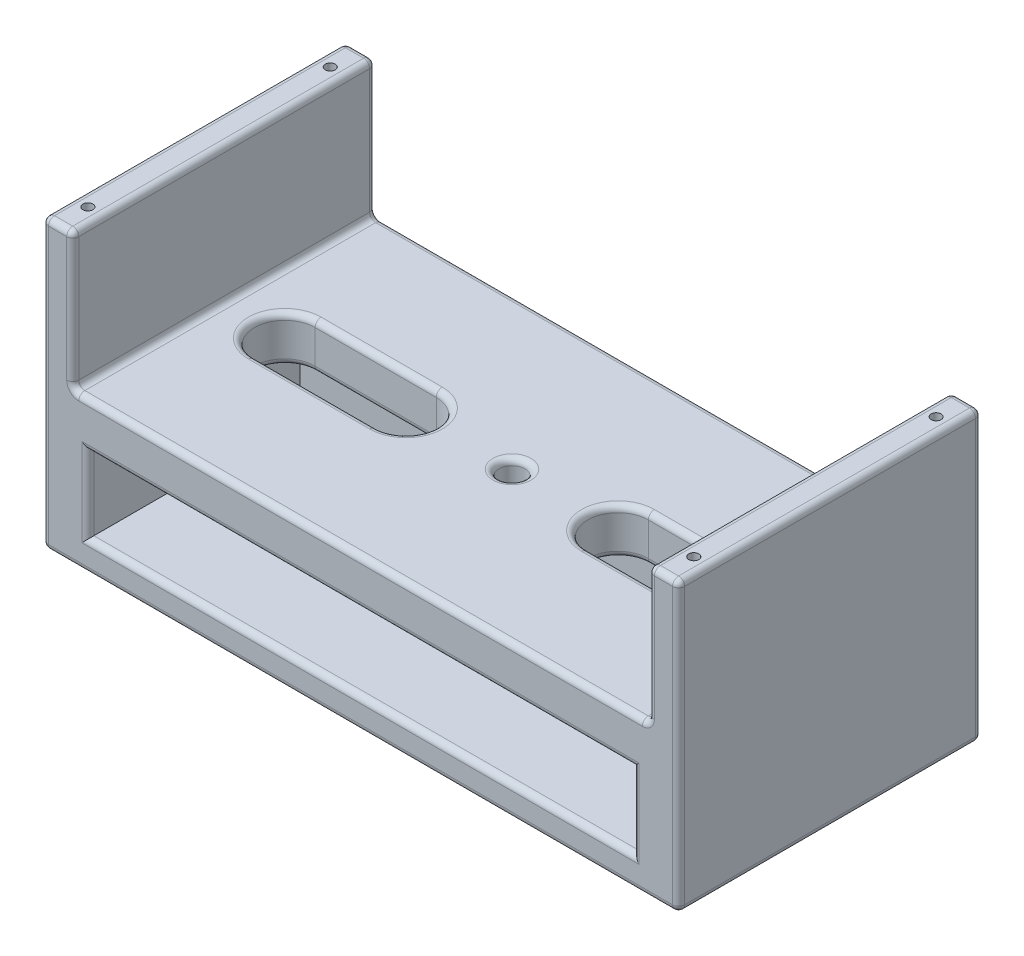
SolidWorks part; units mm, degrees
ref_plane "前视基准面" through (0, 0, 0) normal (0, 0, 1) x (1, 0, 0)
ref_plane "上视基准面" through (0, 0, 0) normal (0, 1, 0) x (1, 0, 0)
ref_plane "右视基准面" through (0, 0, 0) normal (1, 0, 0) x (0, 0, -1)
other "Configuration Table"
sketch "草图1" plane through (0, 0, 0) normal (0, 1, 0) x (1, 0, 0)
  line L1 (0, 0) -> (210, 0)
  line L2 (0, 0) -> (0, -100)
  line L3 (0, -100) -> (210, -100)
  line L4 (210, 0) -> (210, -100)
  dimension "D1" = 210
  dimension "D2" = 100
extrude "凸台-拉伸1" add sketch "草图1" along normal blind 50
sketch "草图2" plane through (0, 50, 0) normal (0, 1, 0) x (1, 0, 0)
  line L0 (0, -50) -> (210, -50) construction
  line L1 (0, 0) -> (0, -100) construction
  line L2 (210, -100) -> (210, 0) construction
  line L3 (105, 0) -> (105, -100) construction
  line L4 (210, 0) -> (0, 0) construction
  line L5 (0, -100) -> (210, -100) construction
  line L6 (30, -50) -> (70, -50) construction
  line L7 (30, -40) -> (70, -40)
  line L8 (30, -60) -> (70, -60)
  line L9 (140, -50) -> (180, -50) construction
  line L10 (140, -40) -> (180, -40)
  line L11 (140, -60) -> (180, -60)
  arc A0 (30, -40) -> (30, -60) centre (30, -50) ccw
  arc A1 (70, -60) -> (70, -40) centre (70, -50) ccw
  arc A2 (140, -40) -> (140, -60) centre (140, -50) ccw
  arc A3 (180, -60) -> (180, -40) centre (180, -50) ccw
  point P12 (105, -50)
  point P15 (50, -50)
  point P20 (160, -50)
  dimension "D3" = 10
  dimension "D1" = 35
  dimension "D2" = 40
  dimension "D4" = 35
extrude "切除-拉伸1" cut sketch "草图2" against normal blind 40
sketch "草图3" plane through (0, 0, 100) normal (0, 0, 1) x (1, 0, 0)
  line L0 (210, 50) -> (210, 0) construction
  line L1 (15, 10) -> (195, 10)
  line L2 (15, 10) -> (15, 35)
  line L3 (15, 35) -> (195, 35)
  line L4 (195, 10) -> (195, 35)
  line L5 (0, 50) -> (0, 0) construction
  line L6 (0, 0) -> (210, 0) construction
  dimension "D1" = 15
  dimension "D2" = 15
  dimension "D3" = 25
  dimension "D4" = 10
extrude "切除-拉伸2" cut sketch "草图3" against normal blind 70
sketch "草图4" plane through (0, 50, 0) normal (0, 1, 0) x (1, 0, 0)
  circle A0 centre (105, -50) radius 4.25
  dimension "D1" = 8.5
extrude "切除-拉伸3" cut sketch "草图4" against normal blind 20
fillet "圆角4" radius 2 18 edges at (190, 50, 50) (160, 50, 60) (130, 50, 50) (130, 35, 50) (160, 35, 60) (190, 35, 50) (80, 50, 50) (50, 50, 60) (20, 50, 50) (20, 35, 50) (50, 35, 60) (80, 35, 50) (160, 50, 40) (160, 35, 40) (50, 50, 40) (50, 35, 40) (105, 35, 54.25) (105, 50, 54.25)
sketch "草图6" plane through (0, 50, 0) normal (0, 1, 0) x (1, 0, 0)
  line L0 (105, 0) -> (105, -100) construction
  line L1 (210, 0) -> (0, 0) construction
  line L2 (0, -100) -> (210, -100) construction
  line L3 (210, -100) -> (200, -100)
  line L4 (0, 0) -> (10, 0)
  line L5 (0, 0) -> (0, -100)
  line L6 (0, -100) -> (10, -100)
  line L7 (10, 0) -> (10, -100)
  line L8 (210, 0) -> (210, -100)
  line L9 (210, 0) -> (200, 0)
  line L10 (200, 0) -> (200, -100)
  circle A0 centre (105, -50) radius 100 construction
  dimension "D1" = 200
  dimension "D2" = 95
extrude "凸台-拉伸2" add sketch "草图6" along normal blind 45
fillet "圆角7" radius 2 28 edges at (0, 95, 50) (0, 0, 50) (210, 95, 50) (210, 0, 50) (200, 95, 50) (200, 50, 50) (10, 95, 50) (10, 50, 50) (210, 47.5, 0) (205, 95, 0) (200, 72.5, 0) (105, 50, 0) (10, 72.5, 0) (5, 95, 0) (0, 47.5, 0) (105, 0, 0) (0, 47.5, 100) (5, 95, 100) (10, 72.5, 100) (105, 50, 100) (200, 72.5, 100) (205, 95, 100) (210, 47.5, 100) (105, 0, 100) (195, 22.5, 100) (105, 35, 100) (15, 22.5, 100) (105, 10, 100)
sketch "草图7" plane through (0, 95, 0) normal (0, 1, 0) x (1, 0, 0)
  line L0 (0, 0) -> (10, 0) construction
  line L1 (0, -98) -> (0, -2) construction
  line L2 (10, -2) -> (10, -98) construction
  line L3 (5, -5.0031) -> (5, -27.7898) construction
  line L4 (8, -100) -> (2, -100) construction
  line L5 (5, -90) -> (205, -90) construction
  line L6 (205, -90) -> (205, -10) construction
  line L7 (202, 0) -> (208, 0) construction
  circle A0 centre (5, -10) radius 1.65
  circle A1 centre (5, -90) radius 1.65
  circle A2 centre (205, -90) radius 1.65
  circle A3 centre (205, -10) radius 1.65
  point P7 (5, 0)
  dimension "D1" = 3.3
  dimension "D4" = 200
  dimension "D2" = 10
  dimension "D3" = 10
  dimension "D5" = 10
extrude "切除-拉伸4" cut sketch "草图7" against normal blind 8
